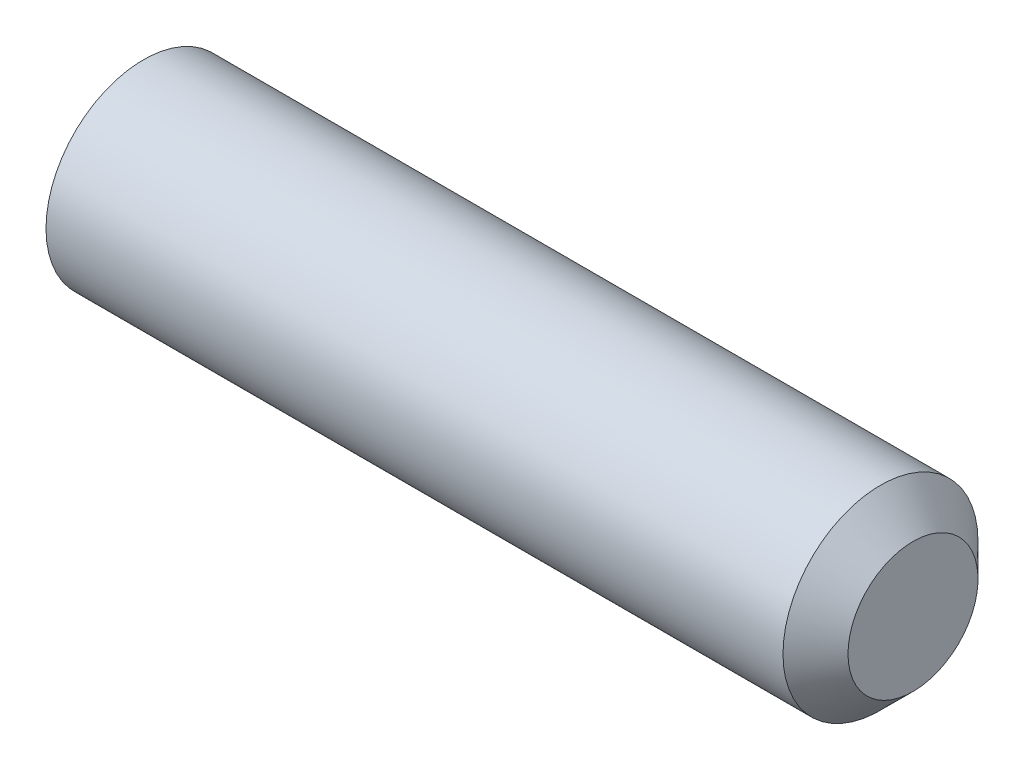
SolidWorks part; units mm, degrees
ref_plane "Plane1" through (0, 0, 0) normal (0, 0, 1) x (1, 0, 0)
ref_plane "Plane2" through (0, 0, 0) normal (0, 1, 0) x (1, 0, 0)
ref_plane "Plane3" through (0, 0, 0) normal (1, 0, 0) x (0, 0, -1)
sketch "BodySke" plane through (0, 0, 0) normal (0, 0, 1) x (1, 0, 0)
  line L0 (0, 0) -> (0, 1.2195)
  line L1 (0, 1.2195) -> (0.1619, 1.5)
  line L2 (0.1619, 1.5) -> (11.5, 1.5)
  line L3 (11.5, 1.5) -> (12, 1)
  line L4 (12, 0) -> (0, 0)
  line L5 (-12.7, 0) -> (88.9, 0) construction
  line L6 (12, 1) -> (12, 0)
  line L7 (12, 1) -> (12, 10.525) construction
  line L8 (0, -1.2195) -> (0.1619, -1.5) construction
  line L9 (0.5, 15.875) -> (0.5, -3.175) construction
  line L10 (11.5, -1.5) -> (12, -1) construction
  dimension "Length" = 12
  dimension "Diameter" = 3
  dimension "Drive_ch_ang" = 60
  dimension "Minor_dia" = 2.439
  dimension "Cup_nose_ang" = 45
  dimension "Cup_dia" = 2
  dimension "Advance" = 0.5
revolve "BaseBody" add sketch "BodySke" angle 360 about L5
cosmetic thread "ThreadCosmetic" [suppressed] parameters "Thread_minor"=2.439
sketch "Sketch2" plane through (0, 0, 0) normal (-1, 0, 0) x (0, 0, 1)
  line L0 (0.433, 0.75) -> (-0.433, 0.75)
  line L1 (-0.433, 0.75) -> (-0.866, 0)
  line L2 (0.433, 0.75) -> (0.866, 0)
  line L3 (0.433, -0.75) -> (0.866, 0)
  line L4 (0.433, -0.75) -> (-0.433, -0.75)
  line L5 (-0.433, -0.75) -> (-0.866, 0)
  dimension "Hex_size" = 1.5
  dimension "D2" = 0.75
  dimension "D3" = 0.75
extrude "Hex" cut sketch "Sketch2" against normal blind 2.1
sketch "Sketch4" plane through (0, 4.7709, -0.5249) normal (-1, 0, 0) x (0, 0, 1)
  line L0 (0.5249, -4.7709) -> (1.3124, -4.7709)
  line L1 (0.5249, -4.7709) -> (6.6732, -1.2211) construction
  line L2 (0.5249, -4.7709) -> (0.9186, -4.0889)
  line L3 (1.153, -4.6137) -> (1.2782, -4.5415)
  line L4 (0.975, -4.3054) -> (1.1002, -4.2332)
  arc A0 (1.153, -4.6137) -> (0.975, -4.3054) centre (0.5249, -4.7709) ccw
  arc A1 (1.3124, -4.7709) -> (1.2782, -4.5415) centre (0.5249, -4.7709) ccw
  arc A2 (0.9186, -4.0889) -> (1.1002, -4.2332) centre (0.5249, -4.7709) cw
  circle A3 centre (0.5249, -4.7709) radius 0.6475 construction
  circle A4 centre (0.5249, -4.7709) radius 0.7875 construction
  dimension "D1" = 30
  dimension "Spline_n_dim" = 1.295
  dimension "Spline_m_dim" = 1.575
  dimension "Spline_a_dim" = 60
  dimension "D3" = 0.178
  dimension "Spline_p_dim" = 0.356
extrude "Spline6" [suppressed] cut sketch "Sketch4" against normal blind 1.2
pattern_circular "CirPattern1" [suppressed] count 6 every 60 about axis through (-12.7, 0, 0) along (1, 0, 0)
sketch "Sketch5" plane through (0, 0.6556, 6.6316) normal (-1, 0, 0) x (0, 0, 1)
  line L0 (-6.6316, -0.6556) -> (-5.8441, -0.6556)
  line L1 (-6.6316, -0.6556) -> (-1.6115, 4.3645) construction
  line L2 (-6.6316, -0.6556) -> (-6.6316, 0.1319)
  line L3 (-6.0479, -0.3236) -> (-5.9633, -0.239)
  line L4 (-6.2996, -0.0719) -> (-6.215, 0.0127)
  line L5 (-6.2996, -0.0719) -> (-6.0479, -0.3236)
  arc A1 (-5.8441, -0.6556) -> (-5.9633, -0.239) centre (-6.6316, -0.6556) ccw
  arc A2 (-6.6316, 0.1319) -> (-6.215, 0.0127) centre (-6.6316, -0.6556) cw
  circle A3 centre (-6.6316, -0.6556) radius 0.6475 construction
  circle A4 centre (-6.6316, -0.6556) radius 0.7875 construction
  dimension "D1" = 45
  dimension "Spline_n_dim" = 1.295
  dimension "Spline_m_dim" = 1.575
  dimension "Spline_a_dim" = 90
  dimension "D3" = 0.178
  dimension "Spline_p_dim" = 0.356
extrude "Spline4" [suppressed] cut sketch "Sketch5" against normal blind 1.2
pattern_circular "CirPattern2" [suppressed] count 4 every 90 about axis through (-12.7, 0, 0) along (1, 0, 0)
sketch "ThdSchSke" plane through (0, 0, 0) normal (0, 0, 1) x (1, 0, 0)
  line L0 (0.1619, -1.2195) -> (-0.0345, -1.5)
  line L1 (0.1619, -1.2195) -> (0.3584, -1.5)
  line L2 (0.3584, -1.5) -> (0.3584, -1.875)
  line L3 (-3.175, 0) -> (5.1513, 0) construction
  line L4 (0.1619, 1.5) -> (0.1619, -1.5) construction
  line L5 (0.3584, -1.875) -> (-0.0345, -1.875)
  line L6 (-0.0345, -1.875) -> (-0.0345, -1.5)
  dimension "Thread_minor" = 2.439
  dimension "Diameter" = 3
  dimension "SideAngle" = 55
  dimension "VeeAngle" = 70
  dimension "Overcut" = 3.75
revolve "ThreadSchematic" [suppressed] cut sketch "ThdSchSke" angle 360 about L3
pattern_linear "ThdSchPat" [suppressed]
equation "\"D2@Sketch2\" = \"Hex_size@Sketch2\" / 2"
equation "\"D3@Sketch2\" = \"Hex_size@Sketch2\" / 2"
equation "\"Thread_minor@ThreadCosmetic\" = \"Minor_dia@BodySke\""
equation "\"D1@Sketch4\" = \"Spline_a_dim@Sketch4\" / 2"
equation "\"D3@Sketch4\" = \"Spline_p_dim@Sketch4\" / 2"
equation "\"D2@CirPattern1\" = \"Spline_a_dim@Sketch4\""
equation "\"Num_teeth@CirPattern1\" = 360 / \"D2@CirPattern1\""
equation "\"Spline_a_dim@Sketch5\" = 90"
equation "\"Spline_p_dim@Sketch5\" = \"Spline_p_dim@Sketch4\""
equation "\"Spline_m_dim@Sketch5\" = \"Spline_m_dim@Sketch4\""
equation "\"Spline_n_dim@Sketch5\" = \"Spline_n_dim@Sketch4\""
equation "\"D1@Sketch5\" = \"Spline_a_dim@Sketch5\" / 2"
equation "\"D3@Sketch5\" = \"Spline_p_dim@Sketch5\" / 2"
equation "\"Key_eng@Spline4\" = \"Key_eng@Spline6\""
equation "\"Thread_minor@ThdSchSke\" = \"Thread_minor@ThreadCosmetic\""
equation "\"Diameter@ThdSchSke\" = \"Diameter@BodySke\""
equation "\"Overcut@ThdSchSke\" = \"Diameter@BodySke\" * 1.25"
equation "\"Num_threads@ThdSchPat\" = int( (\"Length@BodySke\" - ( ( ( \"Diameter@BodySke\" - \"Minor_dia@BodySke\" ) * 0.5 ) / tan( \"Drive_ch_ang@BodySke\" * 0.017453292 ) ) - ( ( ( \"Diameter@BodySke\" - \"Cup_dia@BodySke\" ) * 0.5 ) * tan( \"Cup_nose_ang@BodySke\" * 0.017453292 ) ) ) / \"Advance@BodySke\" + 0.999 )  + 1"
equation "\"Advance@ThdSchPat\" = (\"Length@BodySke\" - ( ( ( \"Diameter@BodySke\" - \"Minor_dia@BodySke\" ) * 0.5 ) / tan( \"Drive_ch_ang@BodySke\" * 0.017453292 ) ) - ( ( ( \"Diameter@BodySke\" - \"Cup_dia@BodySke\" ) * 0.5 ) * tan( \"Cup_nose_ang@BodySke\" * 0.017453292 ) ) ) /  (\"Num_threads@ThdSchPat\" - 1) 'relax it"
equation "' \"Num_threads@ThdSchPat\" = \"Num_threads@ThdSchPat\" - sgn( \"Num_threads@ThdSchPat\" - 1) '---chamfered tips only---"
